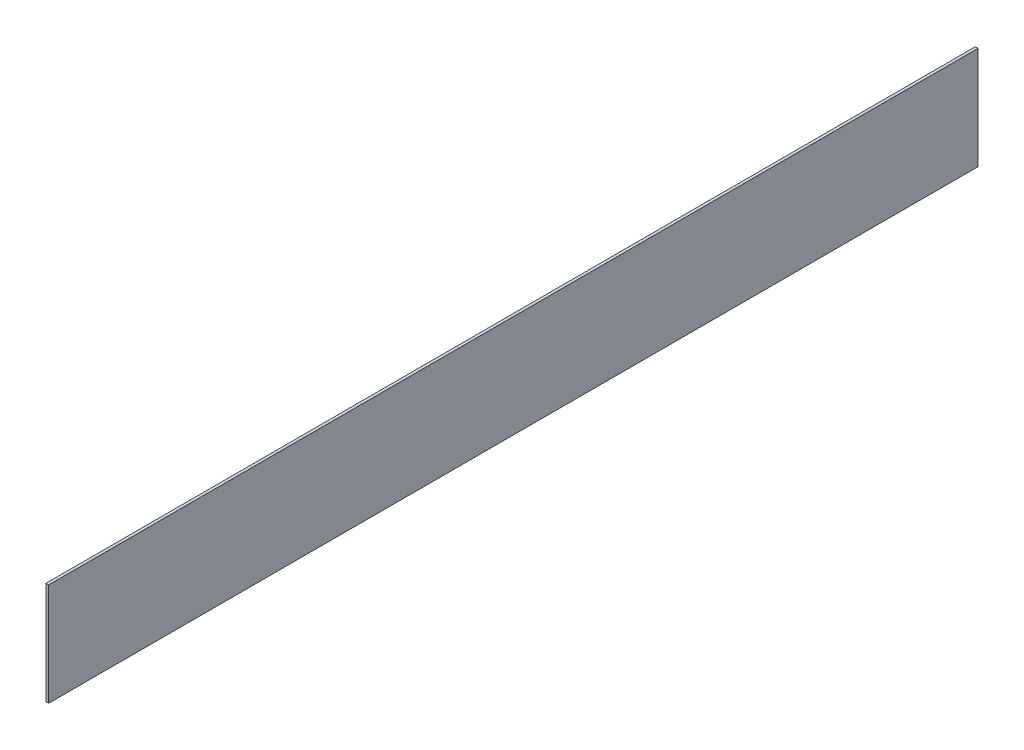
SolidWorks part; units mm, degrees
material "ABS"
ref_plane "Front Plane" through (0, 0, 0) normal (0, 0, 1) x (1, 0, 0)
ref_plane "Top Plane" through (0, 0, 0) normal (0, 1, 0) x (1, 0, 0)
ref_plane "Right Plane" through (0, 0, 0) normal (1, 0, 0) x (0, 0, -1)
other "Configuration Table"
sketch "Sketch1" plane through (0, 0, 0) normal (1, 0, 0) x (0, 0, -1)
  line L1 (68, -7.5) -> (-68, -7.5)
  line L2 (68, -7.5) -> (68, 7.5)
  line L3 (68, 7.5) -> (-68, 7.5)
  line L4 (-68, -7.5) -> (-68, 7.5)
  line L5 (68, -7.5) -> (-68, 7.5) construction
  line L6 (68, 7.5) -> (-68, -7.5) construction
  point P0 (0, 0)
  dimension "D1" = 15
  dimension "D2" = 136
extrude "Boss-Extrude1" add sketch "Sketch1" along normal blind 0.4
